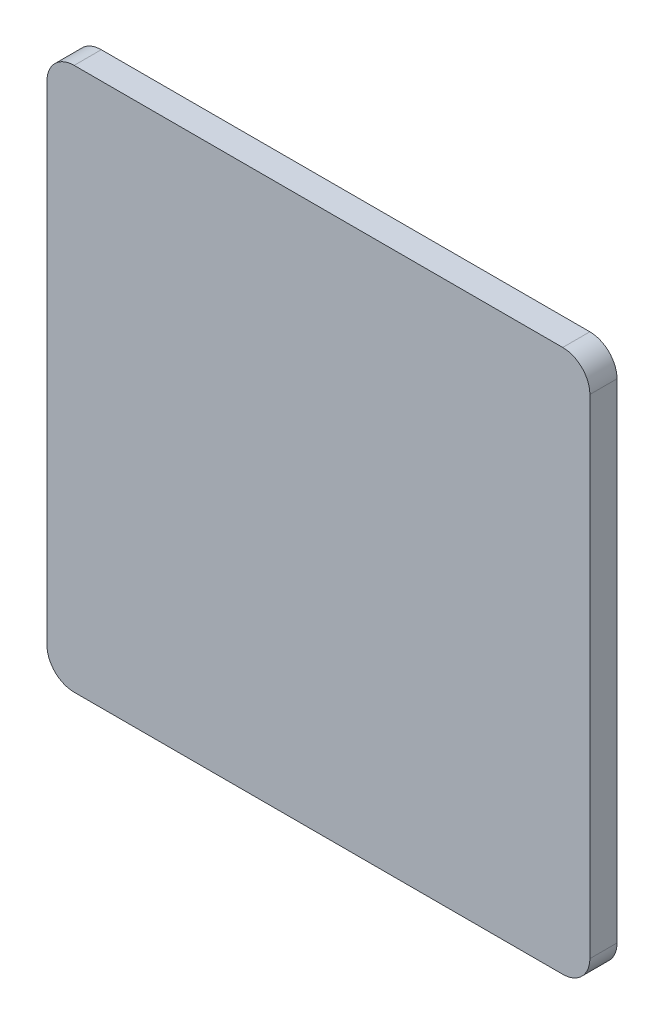
SolidWorks part; units mm, degrees
material "Rubber"
ref_plane "Front Plane" through (0, 0, 0) normal (0, 0, 1) x (1, 0, 0)
ref_plane "Top Plane" through (0, 0, 0) normal (0, 1, 0) x (1, 0, 0)
ref_plane "Right Plane" through (0, 0, 0) normal (1, 0, 0) x (0, 0, -1)
sketch "Sketch1" plane through (0, 0, 0) normal (0, 0, 1) x (1, 0, 0)
  line L1 (0, 0) -> (20, 0)
  line L2 (0, 0) -> (0, 20)
  line L3 (0, 20) -> (20, 20)
  line L4 (20, 0) -> (20, 20)
  dimension "D1" = 20
extrude "Boss-Extrude1" add sketch "Sketch1" along normal blind 1
fillet "Fillet1" radius 1 4 edges at (0, 0, 0.5) (20, 0, 0.5) (20, 20, 0.5) (0, 20, 0.5)
